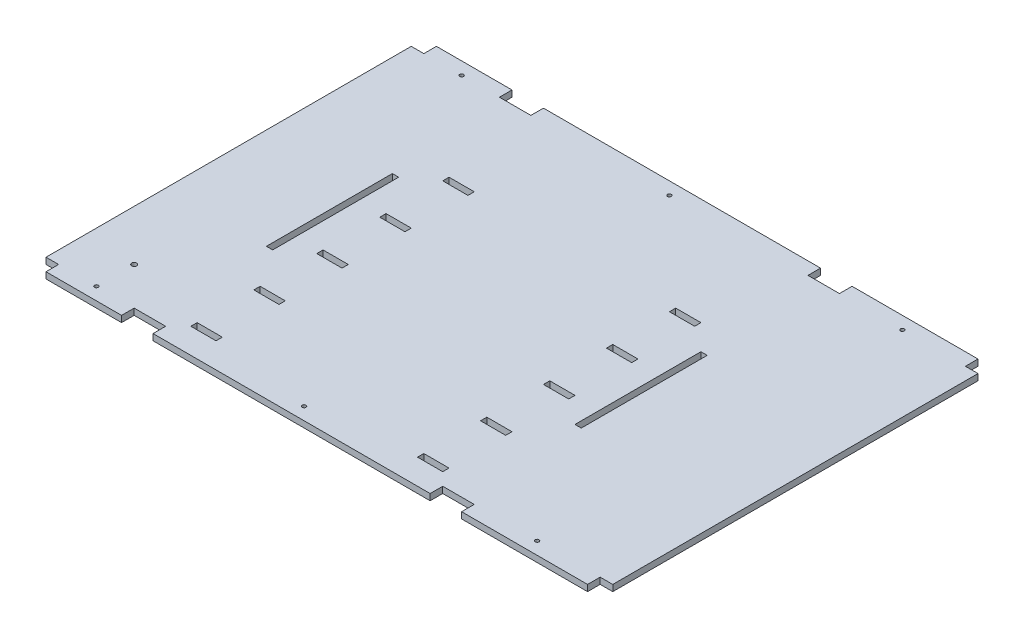
SolidWorks part; units mm, degrees
material "Perspex (TM) GS Acrylic Cast Sheet"
ref_plane "Ebene vorne" through (0, 0, 0) normal (0, 0, 1) x (1, 0, 0)
ref_plane "Ebene oben" through (0, 0, 0) normal (0, 1, 0) x (1, 0, 0)
ref_plane "Ebene rechts" through (0, 0, 0) normal (1, 0, 0) x (0, 0, -1)
sketch "Skizze1" plane through (0, 0, 0) normal (0, 1, 0) x (1, 0, 0)
  line L1 (0, 0) -> (450, 0)
  line L2 (0, 0) -> (0, -310)
  line L3 (0, -310) -> (450, -310)
  line L4 (450, 0) -> (450, -310)
  line L5 (0, 0) -> (450, -310) construction
  line L6 (0, -310) -> (450, 0) construction
  point P4 (225, -155)
  dimension "D1" = 450
  dimension "D2" = 310
extrude "Aufsatz-Linear austragen1" add sketch "Skizze1" along normal blind 5
sketch "Skizze2" plane through (0, 5, 0) normal (0, 1, 0) x (1, 0, 0)
  line L0 (450, 0) -> (0, 0) construction
  line L1 (0, 0) -> (10, 0)
  line L2 (0, 0) -> (0, -10)
  line L3 (0, -10) -> (10, -10)
  line L4 (10, 0) -> (10, -10)
  line L5 (0, 0) -> (10, -10) construction
  line L6 (0, -10) -> (10, 0) construction
  line L7 (10, -10) -> (440, -10) construction
  line L8 (10, -10) -> (10, -300) construction
  line L9 (10, -300) -> (440, -300) construction
  line L10 (440, -10) -> (440, -300) construction
  line L11 (10, -10) -> (440, -300) construction
  line L12 (10, -300) -> (440, -10) construction
  line L13 (440, -300) -> (450, -300)
  line L14 (440, -300) -> (440, -310)
  line L15 (440, -310) -> (450, -310)
  line L16 (450, -300) -> (450, -310)
  line L17 (440, -300) -> (450, -310) construction
  line L18 (440, -310) -> (450, -300) construction
  line L19 (440, -10) -> (450, -10)
  line L20 (440, -10) -> (440, 0)
  line L21 (440, 0) -> (450, 0)
  line L22 (450, -10) -> (450, 0)
  line L23 (440, -10) -> (450, 0) construction
  line L24 (440, 0) -> (450, -10) construction
  line L25 (10, -300) -> (0, -300)
  line L26 (10, -300) -> (10, -310)
  line L27 (10, -310) -> (0, -310)
  line L28 (0, -300) -> (0, -310)
  line L29 (10, -300) -> (0, -310) construction
  line L30 (10, -310) -> (0, -300) construction
  line L31 (70, -10) -> (95, -10)
  line L32 (70, -10) -> (70, 0)
  line L33 (70, 0) -> (95, 0)
  line L34 (95, -10) -> (95, 0)
  line L35 (70, -10) -> (95, 0) construction
  line L36 (70, 0) -> (95, -10) construction
  line L37 (0, -310) -> (450, -310) construction
  line L38 (315, 0) -> (340, 0)
  line L39 (315, 0) -> (315, -10)
  line L40 (315, -10) -> (340, -10)
  line L41 (340, 0) -> (340, -10)
  line L42 (315, 0) -> (340, -10) construction
  line L43 (315, -10) -> (340, 0) construction
  line L44 (340, -300) -> (315, -300)
  line L45 (340, -300) -> (340, -310)
  line L46 (340, -310) -> (315, -310)
  line L47 (315, -300) -> (315, -310)
  line L48 (340, -300) -> (315, -310) construction
  line L49 (340, -310) -> (315, -300) construction
  line L51 (70, -300) -> (95, -300)
  line L52 (70, -300) -> (70, -310)
  line L53 (70, -310) -> (95, -310)
  line L54 (95, -300) -> (95, -310)
  line L55 (70, -300) -> (95, -310) construction
  line L56 (70, -310) -> (95, -300) construction
  point P4 (5, -5)
  point P9 (225, -155)
  point P13 (445, -305)
  point P18 (445, -5)
  point P23 (5, -305)
  point P29 (82.5, -5)
  point P36 (327.5, -5)
  point P41 (327.5, -305)
  point P48 (82.5, -305)
  dimension "D1" = 25
  dimension "D2" = 25
  dimension "D3" = 25
  dimension "D4" = 25
  dimension "D5" = 220
  dimension "D6" = 220
  dimension "D7" = 10
  dimension "D8" = 10
  dimension "D9" = 10
  dimension "D10" = 10
  dimension "D11" = 100
  dimension "D12" = 100
extrude "Schnitt-Linear austragen1" cut sketch "Skizze2" against normal through all
sketch "Skizze3" plane through (0, 5, 0) normal (0, 1, 0) x (1, 0, 0)
  line L0 (82.5, -10) -> (82.5, -300) construction
  line L1 (70, -10) -> (95, -10) construction
  line L2 (95, -300) -> (70, -300) construction
  line L3 (327.5, -10) -> (327.5, -300) construction
  line L4 (315, -10) -> (340, -10) construction
  line L5 (340, -300) -> (315, -300) construction
  line L7 (80, -105) -> (85, -105)
  line L8 (80, -105) -> (80, -205)
  line L9 (80, -205) -> (85, -205)
  line L10 (85, -105) -> (85, -205)
  line L11 (80, -105) -> (85, -205) construction
  line L12 (80, -205) -> (85, -105) construction
  line L13 (325, -105) -> (330, -105)
  line L14 (325, -105) -> (325, -205)
  line L15 (325, -205) -> (330, -205)
  line L16 (330, -105) -> (330, -205)
  line L17 (325, -105) -> (330, -205) construction
  line L18 (325, -205) -> (330, -105) construction
  point P12 (82.5, -155)
  point P17 (327.5, -155)
  dimension "D1" = 5
  dimension "D2" = 100
extrude "Schnitt-Linear austragen2" cut sketch "Skizze3" against normal through all
sketch "Skizze4" plane through (0, 5, 0) normal (0, 1, 0) x (1, 0, 0)
  line L0 (70, -10) -> (95, -10) construction
  line L3 (85, -10) -> (325, -10) construction
  line L4 (85, -10) -> (85, -300) construction
  line L5 (85, -300) -> (325, -300) construction
  line L6 (325, -10) -> (325, -300) construction
  line L7 (340, -300) -> (315, -300) construction
  line L8 (85, -205) -> (85, -105) construction
  line L9 (325, -105) -> (325, -205) construction
  line L10 (85, -290) -> (325, -290) construction
  line L11 (105, -285) -> (125, -285) construction
  line L12 (105, -290) -> (125, -290)
  line L13 (105, -290) -> (105, -285)
  line L14 (105, -285) -> (125, -285)
  line L15 (125, -290) -> (125, -285)
  line L16 (305, -290) -> (285, -290)
  line L17 (305, -290) -> (305, -285)
  line L18 (305, -285) -> (285, -285)
  line L19 (285, -290) -> (285, -285)
  line L20 (105, -285) -> (105, -240) construction
  line L21 (125, -285) -> (125, -240) construction
  line L22 (105, -240) -> (125, -240) construction
  line L23 (125, -240) -> (105, -240)
  line L24 (125, -240) -> (125, -235)
  line L25 (105, -240) -> (105, -235)
  line L26 (125, -235) -> (105, -235)
  line L27 (105, -235) -> (125, -235) construction
  line L28 (105, -235) -> (105, -190) construction
  line L29 (125, -235) -> (125, -190) construction
  line L30 (105, -190) -> (125, -190) construction
  line L31 (125, -190) -> (105, -190)
  line L32 (125, -190) -> (125, -185)
  line L33 (105, -190) -> (105, -185)
  line L34 (125, -185) -> (105, -185)
  line L35 (105, -185) -> (125, -185) construction
  line L36 (105, -185) -> (105, -140) construction
  line L37 (125, -185) -> (125, -140) construction
  line L38 (105, -140) -> (125, -140) construction
  line L39 (125, -140) -> (105, -140)
  line L40 (125, -140) -> (125, -135)
  line L41 (105, -140) -> (105, -135)
  line L42 (125, -135) -> (105, -135)
  line L43 (105, -135) -> (125, -135) construction
  line L44 (105, -135) -> (105, -90) construction
  line L45 (125, -135) -> (125, -90) construction
  line L46 (105, -90) -> (125, -90) construction
  line L47 (125, -90) -> (105, -90)
  line L48 (125, -90) -> (125, -85)
  line L49 (105, -90) -> (105, -85)
  line L50 (125, -85) -> (105, -85)
  line L51 (305, -285) -> (285, -285) construction
  line L52 (305, -285) -> (305, -240) construction
  line L53 (285, -285) -> (285, -240) construction
  line L54 (305, -240) -> (285, -240) construction
  line L55 (305, -240) -> (285, -240)
  line L56 (305, -240) -> (305, -235)
  line L57 (285, -240) -> (285, -235)
  line L58 (305, -235) -> (285, -235)
  line L59 (305, -235) -> (285, -235) construction
  line L60 (305, -235) -> (305, -190) construction
  line L61 (285, -235) -> (285, -190) construction
  line L62 (305, -190) -> (285, -190) construction
  line L63 (305, -190) -> (285, -190)
  line L64 (305, -190) -> (305, -185)
  line L65 (285, -190) -> (285, -185)
  line L66 (305, -185) -> (285, -185)
  line L67 (305, -185) -> (285, -185) construction
  line L68 (305, -185) -> (305, -140) construction
  line L69 (285, -185) -> (285, -140) construction
  line L70 (305, -140) -> (285, -140) construction
  line L71 (305, -140) -> (285, -140)
  line L72 (305, -140) -> (305, -135)
  line L73 (285, -140) -> (285, -135)
  line L74 (305, -135) -> (285, -135)
  line L75 (305, -135) -> (285, -135) construction
  line L76 (305, -135) -> (305, -90) construction
  line L77 (285, -135) -> (285, -90) construction
  line L78 (305, -90) -> (285, -90) construction
  line L79 (305, -90) -> (285, -90)
  line L80 (305, -90) -> (305, -85)
  line L81 (285, -90) -> (285, -85)
  line L82 (305, -85) -> (285, -85)
  point P22 (105, -287.5)
  dimension "D1" = 10
  dimension "D2" = 20
  dimension "D3" = 5
  dimension "D4" = 20
  dimension "D5" = 20
  dimension "D6" = 45
extrude "Schnitt-Linear austragen3" cut sketch "Skizze4" against normal through all
sketch "Skizze5" plane through (0, 5, 0) normal (0, 1, 0) x (1, 0, 0)
  line L1 (10, -10) -> (70, -10) construction
  line L2 (10, -10) -> (10, -300) construction
  line L3 (10, -300) -> (70, -300) construction
  line L4 (70, -10) -> (70, -300) construction
  line L5 (10, -10) -> (70, -300) construction
  line L6 (10, -300) -> (70, -10) construction
  line L7 (95, -10) -> (315, -10) construction
  line L8 (95, -10) -> (95, -300) construction
  line L9 (95, -300) -> (315, -300) construction
  line L10 (315, -10) -> (315, -300) construction
  line L11 (95, -10) -> (315, -300) construction
  line L12 (95, -300) -> (315, -10) construction
  line L13 (340, -10) -> (440, -10) construction
  line L14 (340, -10) -> (340, -300) construction
  line L15 (340, -300) -> (440, -300) construction
  line L16 (440, -10) -> (440, -300) construction
  line L17 (340, -10) -> (440, -300) construction
  line L18 (340, -300) -> (440, -10) construction
  circle A0 centre (40, -10) radius 1.5
  circle A1 centre (205, -10) radius 1.5
  circle A2 centre (390, -10) radius 1.5
  circle A3 centre (40, -300) radius 1.5
  circle A4 centre (205, -300) radius 1.5
  circle A5 centre (390, -300) radius 1.5
  point P6 (40, -155)
  point P13 (205, -155)
  point P20 (390, -155)
  dimension "D1" = 3
extrude "Schnitt-Linear austragen4" cut sketch "Skizze5" against normal through all
sketch "Skizze6" plane through (0, 5, 0) normal (0, 1, 0) x (1, 0, 0)
  line L0 (70, -300) -> (10, -300) construction
  line L1 (70, -300) -> (70, -270) construction
  line L2 (10, -300) -> (10, -270) construction
  line L3 (70, -270) -> (10, -270) construction
  line L4 (70, -300) -> (10, -270) construction
  line L5 (10, -300) -> (70, -270) construction
  circle A0 centre (40, -270) radius 2
  point P8 (40, -285)
  dimension "D2" = 4
  dimension "D1" = 30
extrude "Schnitt-Linear austragen5" cut sketch "Skizze6" against normal through all
